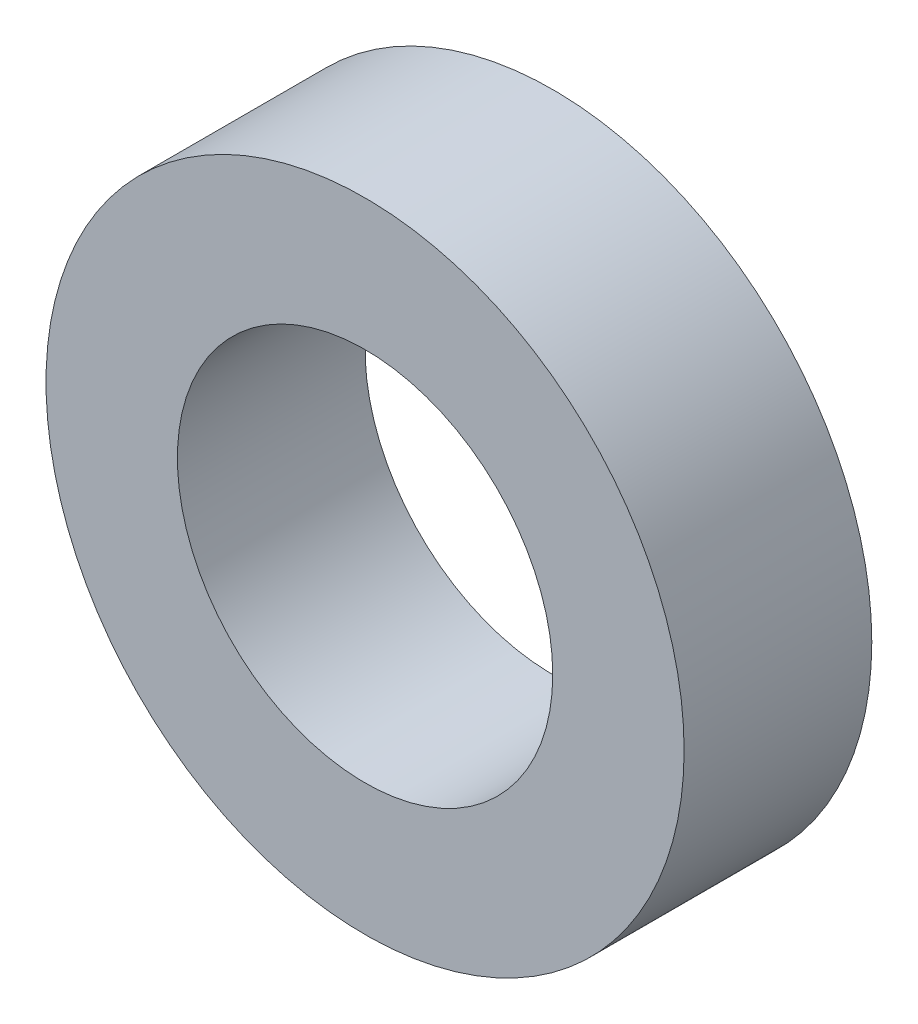
SolidWorks part; units mm, degrees
material "不锈钢 (铁素体)"
ref_plane "前视基准面" through (0, 0, 0) normal (0, 0, 1) x (1, 0, 0)
ref_plane "上视基准面" through (0, 0, 0) normal (0, 1, 0) x (1, 0, 0)
ref_plane "右视基准面" through (0, 0, 0) normal (1, 0, 0) x (0, 0, -1)
sketch "草图1" plane through (0, 0, 0) normal (0, 0, 1) x (1, 0, 0)
  circle A0 centre (0, 0) radius 5
  circle A1 centre (0, 0) radius 8.5
  dimension "D1" = 10
  dimension "D2" = 17
extrude "凸台-拉伸1" add sketch "草图1" along normal blind 5
